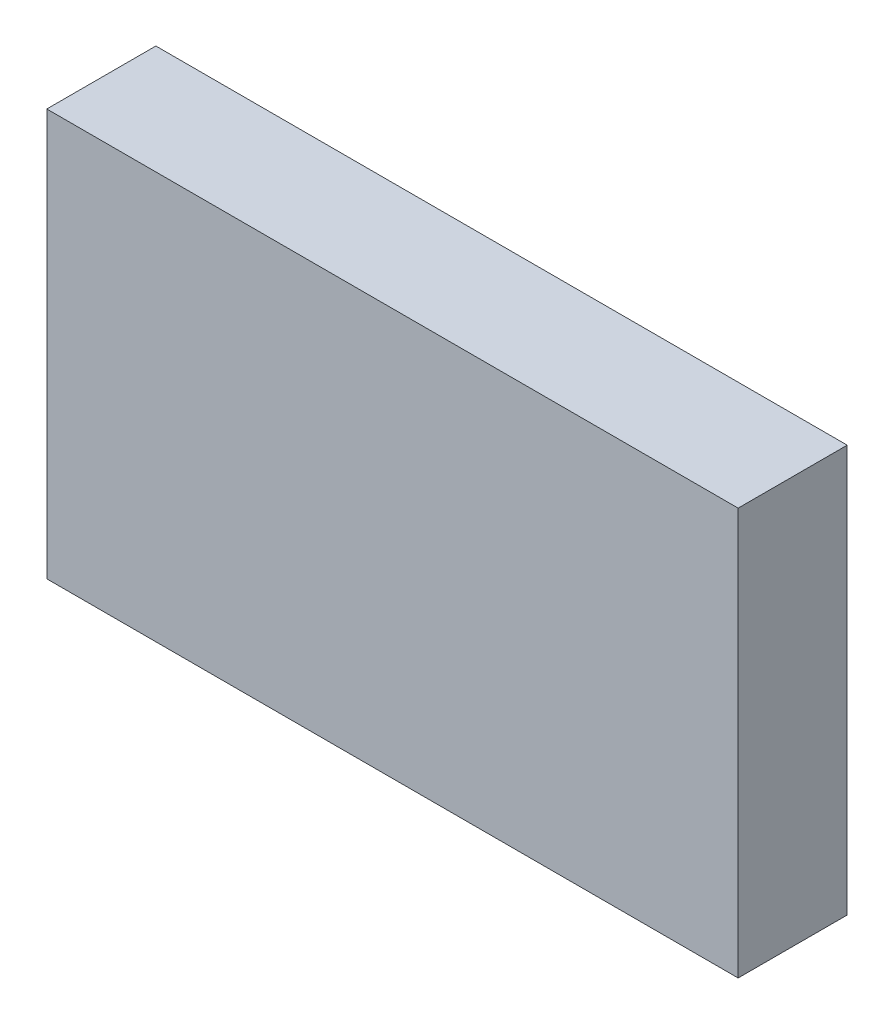
SolidWorks part; units mm, degrees
ref_plane "Front Plane" through (0, 0, 0) normal (0, 0, 1) x (1, 0, 0)
ref_plane "Top Plane" through (0, 0, 0) normal (0, 1, 0) x (1, 0, 0)
ref_plane "Right Plane" through (0, 0, 0) normal (1, 0, 0) x (0, 0, -1)
sketch "Sketch1" plane through (0, 0, 0) normal (0, 0, 1) x (1, 0, 0)
  line L1 (0, 0) -> (63.3898, 0)
  line L2 (0, 0) -> (0, 37.3106)
  line L3 (0, 37.3106) -> (63.3898, 37.3106)
  line L4 (63.3898, 0) -> (63.3898, 37.3106)
extrude "Boss-Extrude1" add sketch "Sketch1" along normal blind 10
